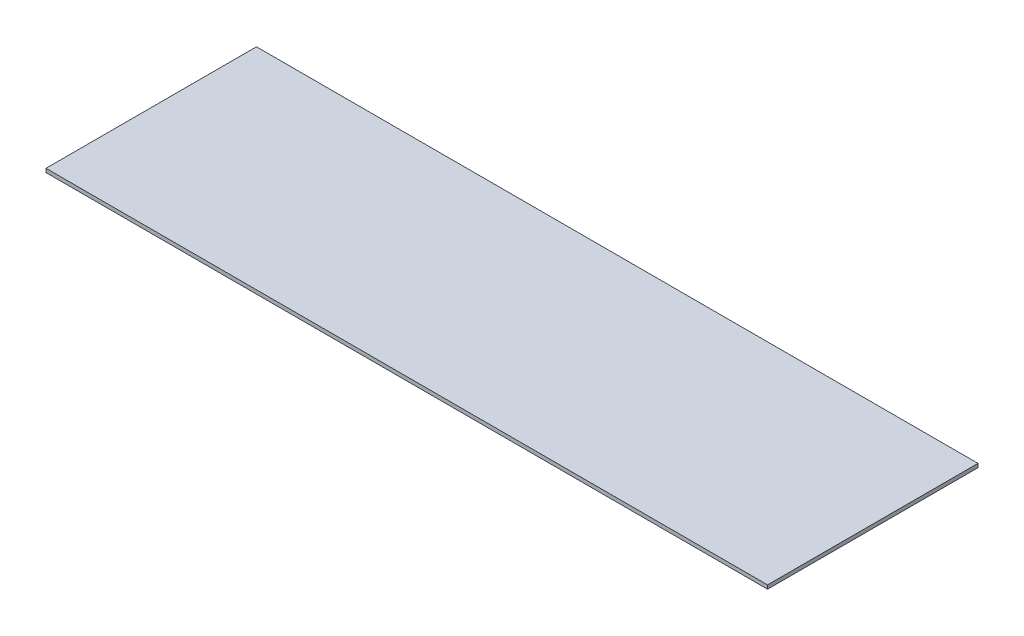
SolidWorks part; units mm, degrees
ref_plane "Front Plane" through (0, 0, 0) normal (0, 0, 1) x (1, 0, 0)
ref_plane "Top Plane" through (0, 0, 0) normal (0, 1, 0) x (1, 0, 0)
ref_plane "Right Plane" through (0, 0, 0) normal (1, 0, 0) x (0, 0, -1)
sketch "Sketch1" plane through (0, 0, 0) normal (0, 1, 0) x (1, 0, 0)
  line L1 (-1219.2, -355.6) -> (1219.2, -355.6)
  line L2 (-1219.2, -355.6) -> (-1219.2, 355.6)
  line L3 (-1219.2, 355.6) -> (1219.2, 355.6)
  line L4 (1219.2, -355.6) -> (1219.2, 355.6)
  line L5 (-1219.2, -355.6) -> (1219.2, 355.6) construction
  line L6 (-1219.2, 355.6) -> (1219.2, -355.6) construction
  point P0 (0, 0)
  dimension "D1" = 711.2
  dimension "D2" = 2438.4
extrude "Boss-Extrude1" add sketch "Sketch1" along normal blind 12.7
equation "\"narrow\"=28"
equation "\"wide\"= 83 / 2"
equation "\"D1@Sketch1\"=\"narrow\""
